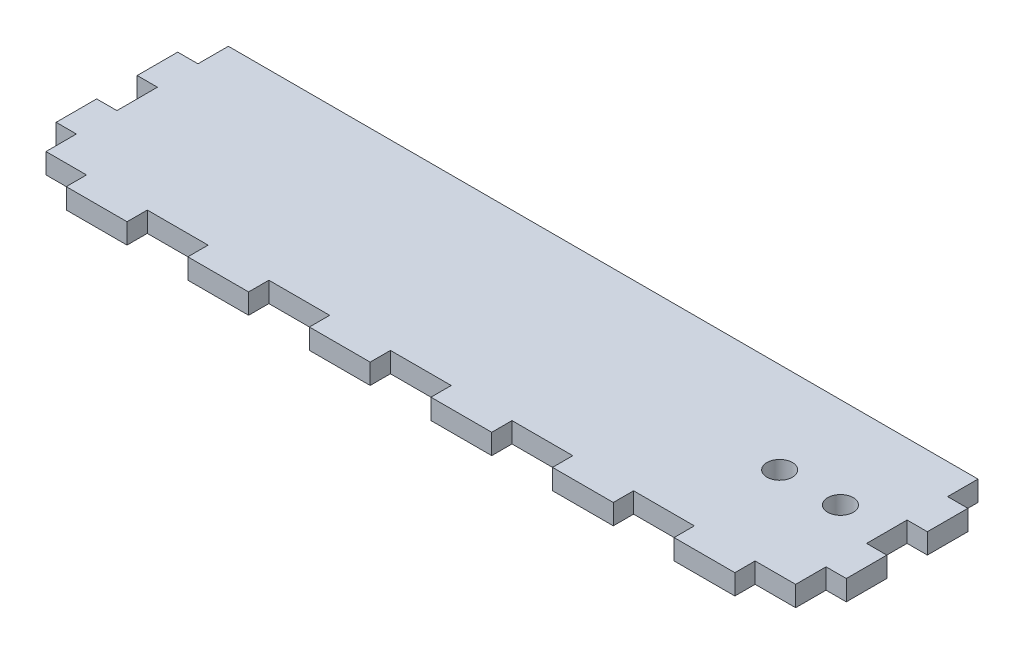
SolidWorks part; units mm, degrees
material "Pin"
ref_plane "Front" through (0, 0, 0) normal (0, 0, 1) x (1, 0, 0)
ref_plane "Top" through (0, 0, 0) normal (0, 1, 0) x (1, 0, 0)
ref_plane "Right" through (0, 0, 0) normal (1, 0, 0) x (0, 0, -1)
sketch "Esquisse1" plane through (0, 0, 0) normal (0, 1, 0) x (1, 0, 0)
  line L1 (-117.475, 28.575) -> (117.475, 28.575)
  line L2 (-117.475, 28.575) -> (-117.475, -28.575)
  line L3 (-117.475, -28.575) -> (117.475, -28.575)
  line L4 (117.475, 28.575) -> (117.475, -28.575)
  line L5 (-117.475, 28.575) -> (117.475, -28.575) construction
  line L6 (-117.475, -28.575) -> (117.475, 28.575) construction
  point P0 (0, 0)
  dimension "D1" = 234.95
  dimension "D2" = 57.15
extrude "Boss.-Extru.1" add sketch "Esquisse1" along normal blind 6.35
sketch "Esquisse2" plane through (0, 6.35, 0) normal (0, 1, 0) x (1, 0, 0)
  line L0 (117.475, -28.575) -> (117.475, 28.575) construction
  circle A0 centre (97.8958, 0) radius 18 construction
  circle A1 centre (83.8958, 0) radius 4
  circle A2 centre (102.9458, 0) radius 4
  point P9 (0, 0)
  dimension "D1" = 36
  dimension "D3" = 8
  dimension "D2" = 19.5792
  dimension "D4" = 19.05
sketch "Esquisse3" plane through (0, 6.35, 0) normal (0, 1, 0) x (1, 0, 0)
  line L0 (-117.475, -28.575) -> (117.475, -28.575) construction
  line L1 (-104.775, -28.575) -> (-85.725, -28.575)
  line L2 (-104.775, -28.575) -> (-104.775, -34.925)
  line L3 (-104.775, -34.925) -> (-85.725, -34.925)
  line L4 (-85.725, -28.575) -> (-85.725, -34.925)
  line L5 (-117.475, 28.575) -> (-117.475, -28.575) construction
  dimension "D1" = 19.05
  dimension "D2" = 6.35
  dimension "D3" = 12.7
extrude "Boss.-Extru.2" add sketch "Esquisse3" against normal blind 6.35
pattern_linear "Répétition linéaire2" count 6 spacing 38.1 along (1, 0, 0) of "Boss.-Extru.2"
sketch "Esquisse5" plane through (0, 6.35, 0) normal (0, 1, 0) x (1, 0, 0)
  line L0 (-117.475, 28.575) -> (-117.475, -28.575) construction
  line L1 (-117.475, -19.05) -> (-123.825, -19.05)
  line L2 (-117.475, -19.05) -> (-117.475, -6.35)
  line L3 (-117.475, -6.35) -> (-123.825, -6.35)
  line L4 (-123.825, -19.05) -> (-123.825, -6.35)
  line L5 (-117.475, -28.575) -> (-104.775, -28.575) construction
  dimension "D1" = 9.525
  dimension "D2" = 6.35
  dimension "D3" = 12.7
extrude "Boss.-Extru.4" add sketch "Esquisse5" against normal blind 6.35
pattern_linear "Répétition linéaire4" count 2 spacing 25.4 along (0, 0, -1) count 2 spacing 241.3 along (1, 0, 0) of "Boss.-Extru.4"
extrude "Enlèv. mat.-Extru.1" cut sketch "Esquisse2" against normal blind 6.35
